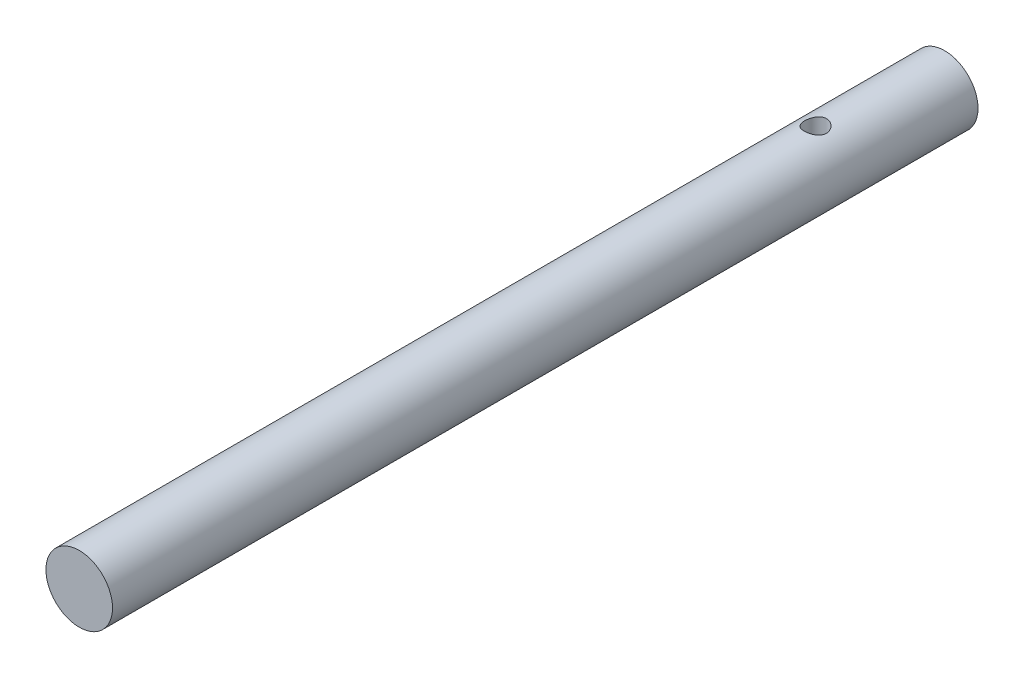
SolidWorks part; units mm, degrees
ref_plane "Front Plane" through (0, 0, 0) normal (0, 0, 1) x (1, 0, 0)
ref_plane "Top Plane" through (0, 0, 0) normal (0, 1, 0) x (1, 0, 0)
ref_plane "Right Plane" through (0, 0, 0) normal (1, 0, 0) x (0, 0, -1)
sketch "Sketch1" plane through (0, 0, 0) normal (0, 0, 1) x (1, 0, 0)
  circle A0 centre (0, 0) radius 5
  dimension "D1" = 10
extrude "Boss-Extrude1" add sketch "Sketch1" along normal blind 130
ref_plane "Plane1" through (0, 5, 0) normal (0, 1, 0) x (1, 0, 0)
sketch "Sketch3" plane through (0, 5, 0) normal (0, 1, 0) x (1, 0, 0)
  point P0 (0, 0)
hole_wizard "M4x0.7 Tapped Hole1" positions "3DSketch3" profile "Sketch4" tap size "M4x0.7" standard "ANSI Metric"
sketch3d "3DSketch3"
  point P0 (-0.05, 4.9997, 19.3649)
  dimension "D1" = 20
sketch "Sketch4" plane through (-0.05, 4.9997, 19.3649) normal (0, 0, 1) x (-0.9999, -0.01, 0)
  line L0 (0, 0) -> (0, 4.9914)
  line L1 (0, 4.9914) -> (1.65, 4)
  line L2 (1.65, 4) -> (1.65, 0)
  line L5 (1.65, 0) -> (0, 0)
  line L10 (0, 4.9914) -> (-1.65, 4) construction
  line L11 (0, -6.35) -> (0, 107.95) construction
  dimension "Tap Drill Dia." = 3.3
  dimension "Tap Drill Depth" = 4
  dimension "Drill Angle" = 118
cosmetic thread "Hole Thread1" parameters "D1"=4, "D2"=4
